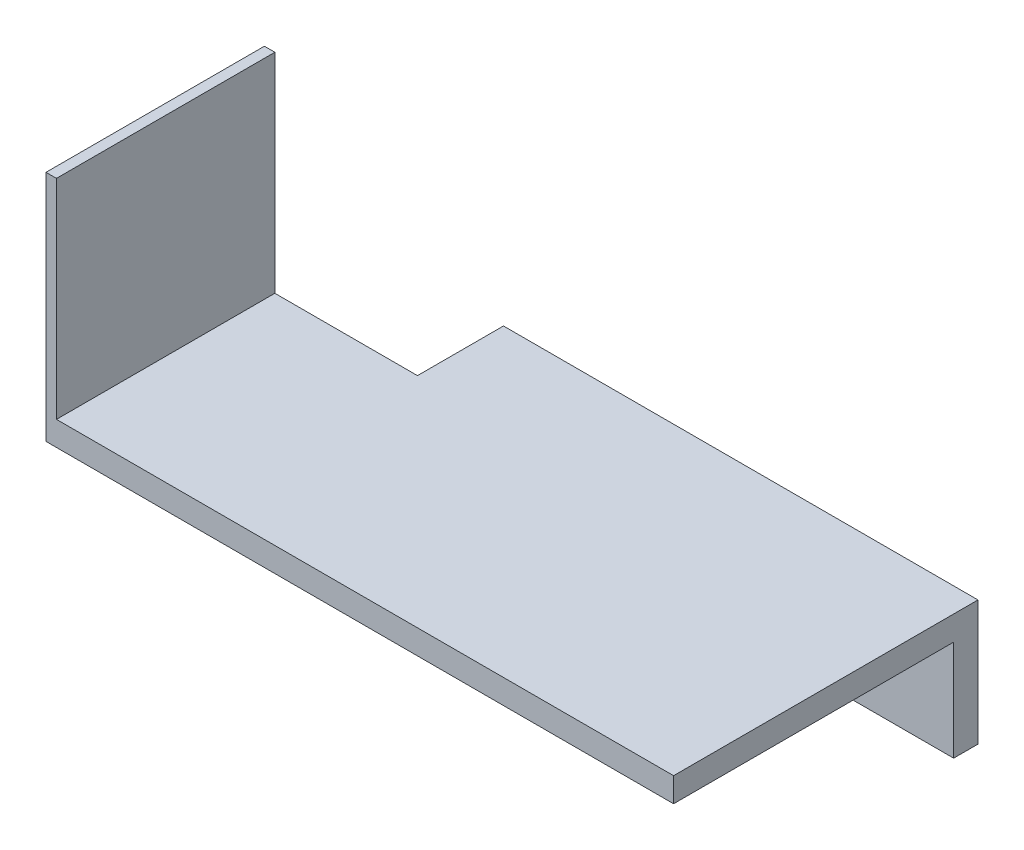
SolidWorks part; units mm, degrees
ref_plane "前基準面" through (0, 0, 0) normal (0, 0, 1) x (1, 0, 0)
ref_plane "上基準面" through (0, 0, 0) normal (0, 1, 0) x (1, 0, 0)
ref_plane "右基準面" through (0, 0, 0) normal (1, 0, 0) x (0, 0, -1)
sketch "草圖1" plane through (0, 0, 0) normal (0, 0, 1) x (1, 0, 0)
  line L1 (34.1, -8.975) -> (-34.1, -8.975)
  line L2 (34.1, -8.975) -> (34.1, 8.975)
  line L3 (34.1, 8.975) -> (-34.1, 8.975)
  line L4 (-34.1, -8.975) -> (-34.1, 8.975)
  line L5 (0, 8.975) -> (0, -8.975) construction
  line L6 (34.1, 0) -> (-34.1, 0) construction
  point P0 (0, 0)
  dimension "D1" = 17.95
  dimension "D2" = 68.2
extrude "1" add sketch "草圖1" along normal blind 3.5
sketch "草圖21" plane through (0, 0, 3.5) normal (0, 0, 1) x (1, 0, 0)
  line L0 (34.1, -8.975) -> (34.1, 8.975) construction
  line L1 (-34.1, 8.975) -> (34.1, 8.975)
  line L2 (-34.1, 8.975) -> (-34.1, 5.475)
  line L3 (-34.1, 5.475) -> (34.1, 5.475)
  line L4 (34.1, 8.975) -> (34.1, 5.475)
  dimension "D1" = 3.5
extrude "填料-伸長4" add sketch "草圖21" along normal blind 28.25
sketch "草圖24" plane through (0, 0, 0) normal (0, 0, -1) x (-1, 0, 0)
  line L0 (0, -8.975) -> (0, -5.975) construction
  line L1 (34.1, -8.975) -> (-34.1, -8.975) construction
  circle A0 centre (0, -3.0705) radius 2.85
  dimension "D1" = 5.7
extrude "除料-伸長2" cut sketch "草圖24" against normal blind 28.25
sketch "草圖30" plane through (0, 0, 31.75) normal (0, 0, 1) x (1, 0, 0)
  line L1 (34.1, 8.975) -> (-34.1, 8.975)
  line L2 (34.1, 8.975) -> (34.1, 5.475)
  line L3 (34.1, 5.475) -> (-34.1, 5.475)
  line L4 (-34.1, 8.975) -> (-34.1, 5.475)
extrude "填料-伸長6" add sketch "草圖30" along normal blind 12
sketch "草圖31" plane through (-34.1, 0, 0) normal (-1, 0, 0) x (0, 0, 1)
  line L0 (43.75, 5.475) -> (3.5, 5.475) construction
  line L1 (12.3614, 5.475) -> (43.75, 5.475)
  line L2 (12.3614, 5.475) -> (12.3614, 8.975)
  line L3 (12.3614, 8.975) -> (43.75, 8.975)
  line L4 (43.75, 5.475) -> (43.75, 8.975)
extrude "填料-伸長7" add sketch "草圖31" along normal blind 22
sketch "草圖32" plane through (0, 8.975, 0) normal (0, 1, 0) x (1, 0, 0)
  line L0 (34.1, -43.75) -> (-56.1, -43.75) construction
  line L1 (-56.1, -12.3614) -> (-54.5965, -12.3614)
  line L2 (-56.1, -12.3614) -> (-56.1, -43.75)
  line L3 (-56.1, -43.75) -> (-54.5965, -43.75)
  line L4 (-54.5965, -12.3614) -> (-54.5965, -43.75)
  dimension "D1" = 1.5035
extrude "填料-伸長8" add sketch "草圖32" along normal blind 30
